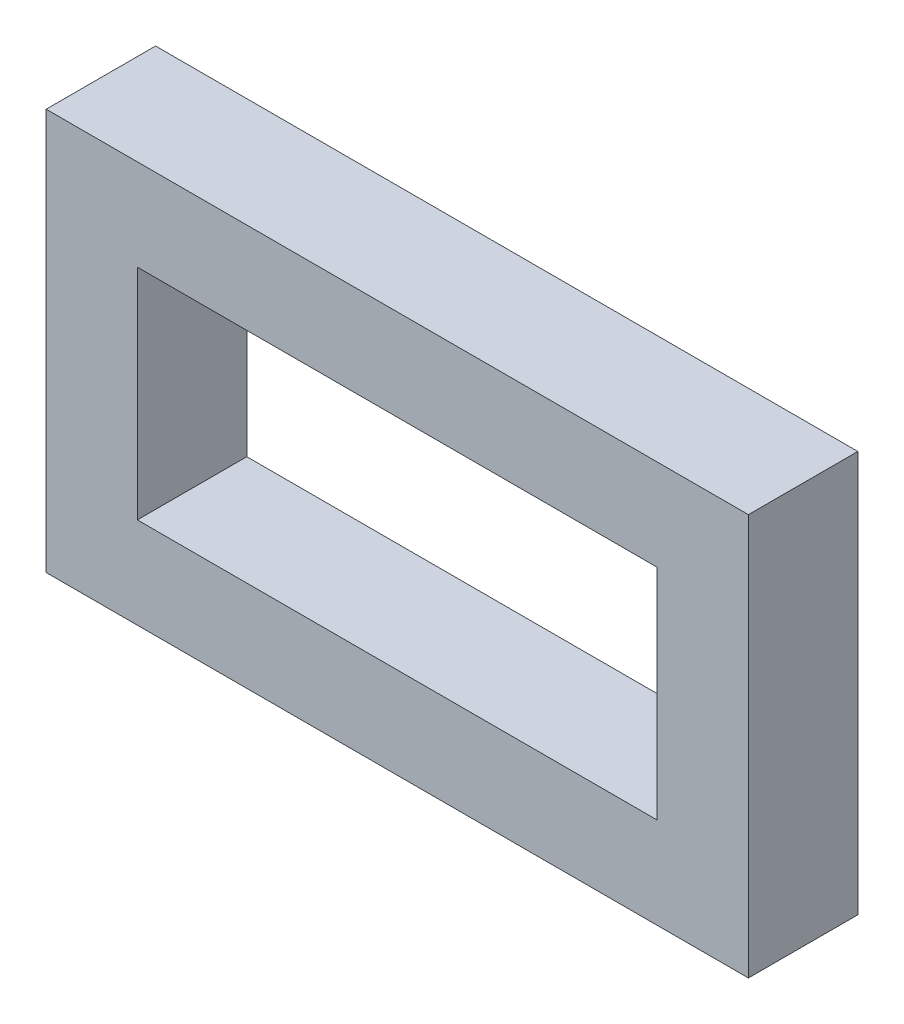
SolidWorks part; units mm, degrees
ref_plane "Plan de face" through (0, 0, 0) normal (0, 0, 1) x (1, 0, 0)
ref_plane "Plan de dessus" through (0, 0, 0) normal (0, 1, 0) x (1, 0, 0)
ref_plane "Plan de droite" through (0, 0, 0) normal (1, 0, 0) x (0, 0, -1)
sketch "Esquisse1" plane through (0, 0, 0) normal (0, 0, 1) x (1, 0, 0)
  line L1 (-19.25, 11) -> (19.25, 11)
  line L2 (-19.25, 11) -> (-19.25, -11)
  line L3 (-19.25, -11) -> (19.25, -11)
  line L4 (19.25, 11) -> (19.25, -11)
  line L7 (-14.25, 6) -> (14.25, 6)
  line L8 (-14.25, 6) -> (-14.25, -6)
  line L9 (-14.25, -6) -> (14.25, -6)
  line L10 (14.25, 6) -> (14.25, -6)
  line L11 (-14.25, 6) -> (14.25, -6) construction
  line L12 (-14.25, -6) -> (14.25, 6) construction
  point P0 (0, 0)
  point P6 (0, 0)
  dimension "D1" = 28.5
  dimension "D2" = 12
  dimension "D3" = 5
  dimension "D4" = 5
  dimension "D5" = 5
  dimension "D6" = 5
extrude "Boss.-Extru.1" add sketch "Esquisse1" along normal blind 6
